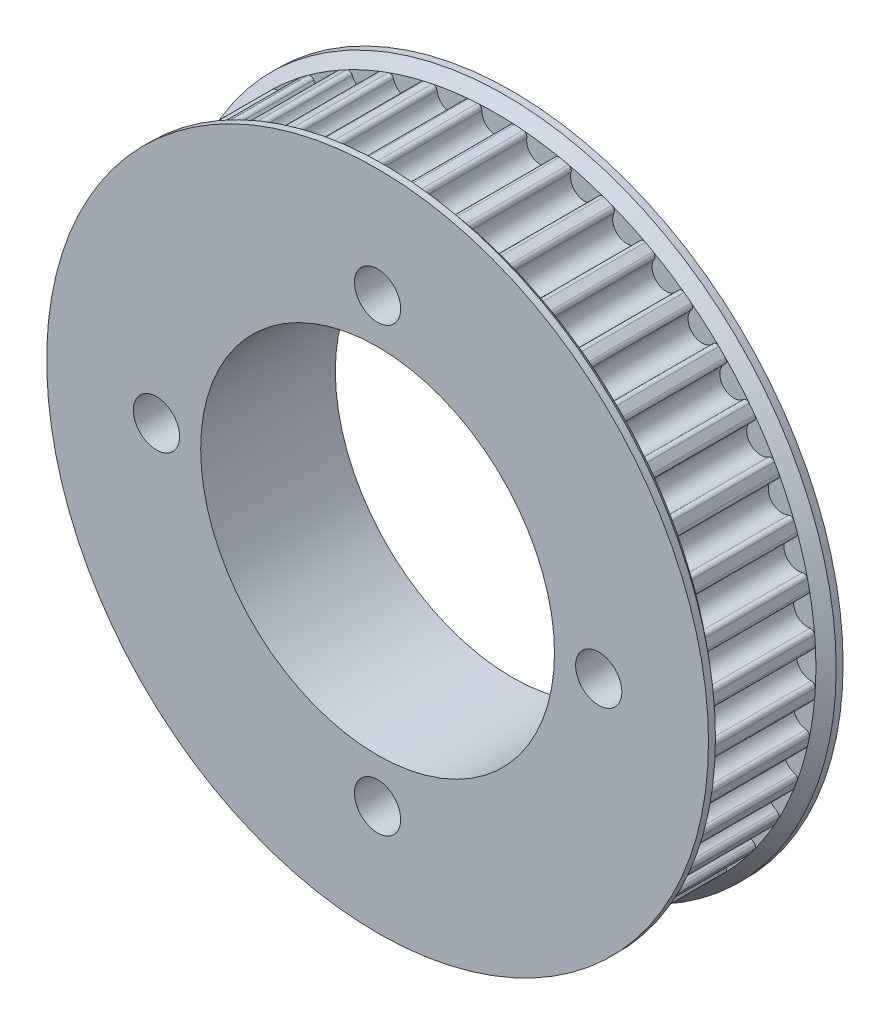
SolidWorks part; units mm, degrees
material "Nailon 6/10"
ref_plane "Alzado" through (0, 0, 0) normal (0, 0, 1) x (1, 0, 0)
ref_plane "Planta" through (0, 0, 0) normal (0, 1, 0) x (1, 0, 0)
ref_plane "Vista lateral" through (0, 0, 0) normal (1, 0, 0) x (0, 0, -1)
sketch "Croquis2" plane through (0, 0, 0) normal (0, 0, 1) x (1, 0, 0)
  circle A0 centre (0, 0) radius 34.4426
  dimension "D1" = 68.8852
extrude "Saliente-Extruir1" add sketch "Croquis2" along normal mid plane 11
sketch "Croquis4" plane through (0, 0, 0) normal (0, 0, 1) x (1, 0, 0)
  line L0 (0, 0) -> (0, 33.9076) construction
  line L1 (0, 0) -> (4.8256, 33.5625) construction
  circle A0 centre (0, 0) radius 32.3826
  circle A1 centre (0, 33.9076) radius 1.525 construction
  circle A2 centre (4.8256, 33.5625) radius 1.525 construction
  circle A3 centre (1.9544, 33.9564) radius 0.43 construction
  circle A4 centre (0, 0) radius 34.4426 construction
  circle A5 centre (2.898, 33.8889) radius 0.43 construction
  arc A6 (-1.5245, 33.9457) -> (1.5245, 33.9457) centre (0, 33.9076) ccw
  arc A7 (1.5245, 33.9457) -> (1.9791, 34.3857) centre (1.9544, 33.9564) cw
  arc A8 (2.9346, 34.3173) -> (1.9791, 34.3857) centre (0, 0) ccw
  arc A9 (2.9346, 34.3173) -> (3.322, 33.8171) centre (2.898, 33.8889) cw
  arc A10 (3.322, 33.8171) -> (4.6085, 32.053) centre (4.8256, 33.5625) ccw
  arc A11 (-3.322, 33.8171) -> (-4.6085, 32.053) centre (-4.8256, 33.5625) cw
  arc A12 (-2.9346, 34.3173) -> (-3.322, 33.8171) centre (-2.898, 33.8889) ccw
  arc A13 (-2.9346, 34.3173) -> (-1.9791, 34.3857) centre (0, 0) cw
  arc A14 (-1.5245, 33.9457) -> (-1.9791, 34.3857) centre (-1.9544, 33.9564) ccw
  arc A15 (-1.9791, 34.3857) -> (1.9791, 34.3857) centre (0, 0) cw
  dimension "D1" = 64.7652
  dimension "D3" = 3.05
  dimension "D4" = 0.86
  dimension "D2" = 8.182
extrude "Cortar-Extruir2" cut sketch "Croquis4" against normal through all both and the other way through all contours A15 A14 A6 A7
pattern_circular "MatrizC4" count 44 over 360 about axis through (0, 0, 0) along (0, 0, 1) of "Cortar-Extruir2"
sketch "Croquis5" plane through (0, 0, 0) normal (0, 1, 0) x (1, 0, 0)
  line L0 (0, 0) -> (0, 5.5) construction
  line L1 (1.525, 5.5) -> (-1.525, 5.5) construction
  line L2 (0, 5.5) -> (34.4426, 5.5)
  line L3 (34.4426, 5.5) -> (35.6343, 6.5)
  line L4 (35.6343, 6.5) -> (35.6343, 7.25)
  line L5 (35.6343, 7.25) -> (0, 7.25)
  line L6 (0, 7.25) -> (0, 5.5)
  line L7 (0, 0) -> (34.4426, 0) construction
  line L9 (0, -7.25) -> (0, -5.5)
  line L10 (35.6343, -7.25) -> (0, -7.25)
  line L11 (35.6343, -6.5) -> (35.6343, -7.25)
  line L12 (34.4426, -5.5) -> (35.6343, -6.5)
  line L13 (0, -5.5) -> (34.4426, -5.5)
  dimension "D1" = 50
  dimension "D2" = 1.75
  dimension "D3" = 0.75
  dimension "D4" = 68.8852
revolve "Revolución1" add sketch "Croquis5" angle 360 about L0
sketch "Croquis6" plane through (0, 0, 0) normal (0, 0, 1) x (1, 0, 0)
  line L1 (3.6882, -6.3881) -> (7.3763, 0)
  line L2 (7.3763, 0) -> (3.6882, 6.3881)
  line L3 (3.6882, 6.3881) -> (-2.9954, 6.3881)
  line L4 (-4.0346, 5.7881) -> (-7.3763, 0)
  line L5 (-7.3763, 0) -> (-3.6882, -6.3881)
  line L6 (-3.6882, -6.3881) -> (3.6882, -6.3881)
  line L7 (-3.6882, 6.3881) -> (-7.3763, 0)
  line L8 (-7.3763, 0) -> (-3.6882, -6.3881)
  line L9 (-3.6882, -6.3881) -> (3.6882, -6.3881)
  line L10 (3.6882, -6.3881) -> (7.3763, 0)
  line L11 (7.3763, 0) -> (3.6882, 6.3881)
  line L12 (3.6882, 6.3881) -> (-3.6882, 6.3881)
  circle A0 centre (0, 0) radius 6.3881 construction
  arc A1 (-3.3418, 6.5881) -> (-4.0346, 6.1881) centre (-3.6882, 6.3881) ccw
  arc A2 (-4.0346, 5.7881) -> (-4.0346, 6.1881) centre (-4.381, 5.9881) ccw
  arc A3 (-2.9954, 6.3881) -> (-3.3418, 6.5881) centre (-2.9954, 6.7881) cw
  circle A4 centre (0, 0) radius 6.3881 construction
  arc A5 (4.0346, 5.7881) -> (4.0346, 6.1881) centre (4.381, 5.9881) cw
  arc A6 (4.0346, 6.1881) -> (3.3418, 6.5881) centre (3.6882, 6.3881) ccw
  arc A7 (2.9954, 6.3881) -> (3.3418, 6.5881) centre (2.9954, 6.7881) ccw
  arc A8 (7.0299, -0.6) -> (7.3763, -0.4) centre (7.3763, -0.8) cw
  arc A9 (7.3763, -0.4) -> (7.3763, 0.4) centre (7.3763, 0) ccw
  arc A10 (7.0299, 0.6) -> (7.3763, 0.4) centre (7.3763, 0.8) ccw
  arc A11 (2.9954, -6.3881) -> (3.3418, -6.5881) centre (2.9954, -6.7881) cw
  arc A12 (3.3418, -6.5881) -> (4.0346, -6.1881) centre (3.6882, -6.3881) ccw
  arc A13 (4.0346, -5.7881) -> (4.0346, -6.1881) centre (4.381, -5.9881) ccw
  arc A14 (-4.0346, -5.7881) -> (-4.0346, -6.1881) centre (-4.381, -5.9881) cw
  arc A15 (-4.0346, -6.1881) -> (-3.3418, -6.5881) centre (-3.6882, -6.3881) ccw
  arc A16 (-2.9954, -6.3881) -> (-3.3418, -6.5881) centre (-2.9954, -6.7881) ccw
  arc A17 (-7.0299, 0.6) -> (-7.3763, 0.4) centre (-7.3763, 0.8) cw
  arc A18 (-7.3763, 0.4) -> (-7.3763, -0.4) centre (-7.3763, 0) ccw
  arc A19 (-7.0299, -0.6) -> (-7.3763, -0.4) centre (-7.3763, -0.8) ccw
  point P54 (0, 0)
  dimension "D1" = 12.7762
  dimension "D2" = 0.8
  dimension "D3" = 0.4
  dimension "D4" = 0.4
  dimension "D5" = 6
extrude "Cortar-Extruir3" cut sketch "Croquis6" against normal through all both and the other way through all contours L3 L12 L7 L4 L5 L8 L6 L9 L1 L10 L2 L11 | A7 L3 L11 A5 A6 | L12 A3 A1 A2 L7 | A19 L5 L7 A17 A18 | A16 L6 L8 A14 A15 | A13 L1 L9 A11 A12 | A10 L2 L10 A8 A9
sketch "Croquis7" plane through (0, 0, 7.25) normal (0, 0, 1) x (1, 0, 0)
  line L0 (0, 0) -> (0, 23.8125) construction
  line L1 (0, 0) -> (0, 23.8125) construction
  circle A0 centre (0, 23.8125) radius 2.4892
  circle A1 centre (23.8125, 0) radius 2.4892
  circle A2 centre (0, -23.8125) radius 2.4892
  circle A3 centre (-23.8125, 0) radius 2.4892
  circle A4 centre (0, 0) radius 19.05
  dimension "D1" = 23.8125
  dimension "D2" = 4.9784
  dimension "D5" = 38.1
  dimension "D4" = 23.8125
  dimension "D3" = 4
extrude "Cortar-Extruir4" cut sketch "Croquis7" against normal up to surface (14.5 mm away) contours A4 | A3 | A0 | A2 | A1 up to face at (35.6343, 0, -7.25)
equation "\"X\"= \"DimCal\""
equation "\"Y\"= \"X\" - ( 2 * 2.06 )"
equation "\"Nt\"= 44'Numero de dientes ( Minimo 10 reco 18)"
equation "\"A\"= 360° / \"Nt\""
equation "\"G\"= 11mm"
equation "\"D1@Croquis2\"=\"X\""
equation "\"D1@Saliente-Extruir1\"=\"G\""
equation "\"D1@Croquis4\"=\"Y\""
equation "\"D2@Croquis4\"=\"A\""
equation "\"D1@MatrizC4\"=\"Nt\""
equation "\"TP\"= 5mm'Tooth pitch"
equation "\"PLO\"= 0.5715mm'Pitch line offset"
equation "\"DimCal\"= 2 * ( ( \"Nt\" * \"TP\" ) / ( pi * 2 ) - \"PLO\" )'Diameter (calculated)"
equation "\"D4@Croquis5\"=\"X\""
